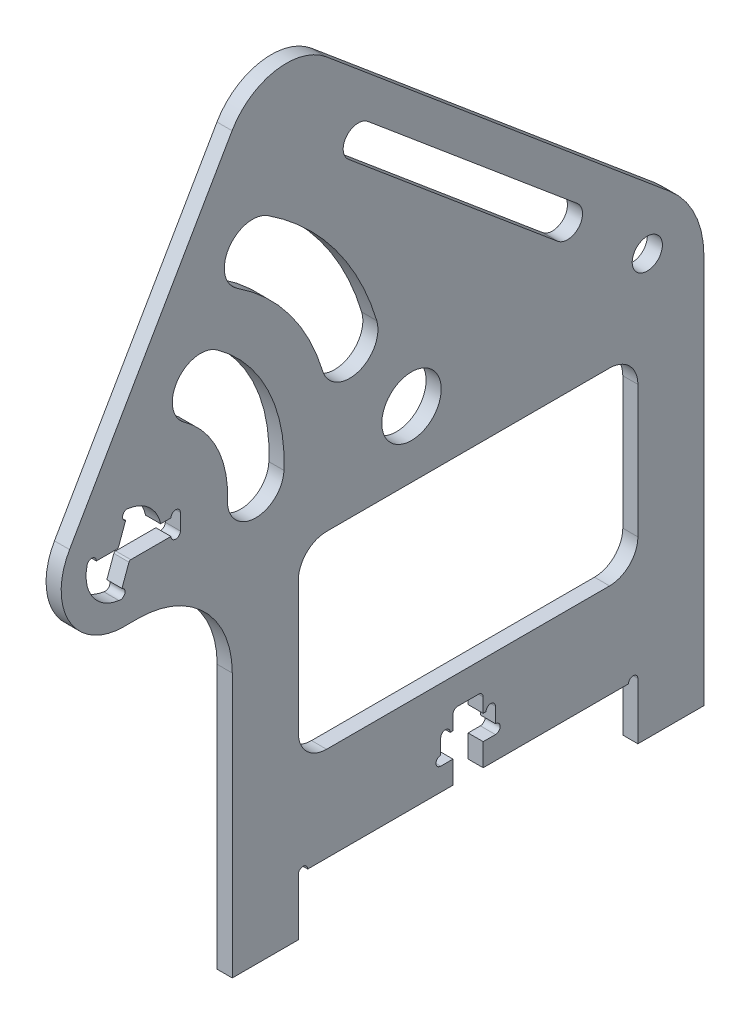
SolidWorks part; units mm, degrees
material "Thornel VCB-20 Carbon Cloth"
ref_plane "Front" through (0, 0, 0) normal (0, 0, 1) x (1, 0, 0)
ref_plane "Top" through (0, 0, 0) normal (0, 1, 0) x (1, 0, 0)
ref_plane "Right" through (0, 0, 0) normal (1, 0, 0) x (0, 0, -1)
sketch "Sketch1" plane through (0, 0, 0) normal (1, 0, 0) x (0, 0, -1)
  line L0 (-25, 0) -> (25, 0)
  line L1 (25, 0) -> (25, 40)
  line L2 (25, 40) -> (-21.0649, 78.653)
  line L3 (-21.0649, 78.653) -> (-48, 32)
  line L4 (-48, 32) -> (-25, 32)
  line L5 (-25, 32) -> (-25, 0)
  dimension "D1" = 50
  dimension "D2" = 32
  dimension "D3" = 60
  dimension "D4" = 40
  dimension "D5" = 40
  dimension "D6" = 23
extrude "main body" add sketch "Sketch1" against normal mid plane 1.6
sketch "Sketch2" plane through (0, 0, 0) normal (1, 0, 0) x (0, 0, -1)
  line L0 (0, 0) -> (0, -15.3449) construction
  line L1 (-25, 0) -> (-25, -6)
  line L2 (25, 0) -> (25, -6)
  line L3 (-25, -6) -> (-18, -6)
  line L4 (25, -6) -> (18, -6)
  line L5 (-18, -6) -> (-18, 0)
  line L6 (-25, 0) -> (25, 0) construction
  line L7 (18, -6) -> (18, 0)
  line L8 (-18, 0) -> (-25, 0)
  line L9 (18, 0) -> (25, 0)
  dimension "D1" = 7
  dimension "D2" = 6
extrude "slot tabs" add sketch "Sketch2" along normal up to surface and the other way up to surface up to face at (0.8, 30.4422, 11.5108) other way up to face at (-0.8, 30.4422, 11.5108)
sketch "Sketch10" [suppressed] plane through (0.8, 0, 0) normal (1, 0, 0) x (0, 0, -1)
  line L0 (-18, 0) -> (18, 0) construction
  line L1 (-18, 0) -> (18, 0) construction
  circle A0 centre (-17.2, 0) radius 0.8
  circle A1 centre (17.2, 0) radius 0.8
  dimension "D1" = 1.6
extrude "slot dogs" [suppressed] cut sketch "Sketch10" against normal through all
sketch "Sketch3" plane through (0, 0, 0) normal (1, 0, 0) x (0, 0, -1)
  line L0 (-1.6, 2.4) -> (-1.6, 0)
  line L1 (-1.6, 2.4) -> (1.6, 2.4) construction
  line L2 (-1.6, 0) -> (1.6, 0)
  line L3 (1.6, 2.4) -> (1.6, 0)
  line L4 (-1.6, 2.4) -> (1.6, 0) construction
  line L5 (-1.6, 0) -> (1.6, 2.4) construction
  line L6 (-18, 0) -> (18, 0) construction
  line L7 (-2.9, 2.4) -> (-1.6, 2.4)
  line L8 (2.9, 5) -> (-2.9, 5)
  line L9 (2.9, 5) -> (2.9, 2.4)
  line L10 (1.6, 2.4) -> (2.9, 2.4)
  line L11 (-2.9, 5) -> (-2.9, 2.4)
  line L12 (2.9, 5) -> (-2.9, 2.4) construction
  line L13 (2.9, 2.4) -> (-2.9, 5) construction
  line L14 (-1.6, 2.4) -> (2.9, 2.4) construction
  point P1 (0, 1.2)
  point P3 (0, 3.7)
  dimension "D1" = 3.2
  dimension "D2" = 2.4
  dimension "D3" = 5.8
  dimension "D4" = 2.6
extrude "attachment t-slot" cut sketch "Sketch3" against normal through all and the other way through all
sketch "camera slot positioning" plane through (0, 0, 0) normal (1, 0, 0) x (0, 0, -1)
  line L0 (-11.6418, 64.2191) -> (19, 38.5076)
  line L1 (25, 40) -> (-21.0649, 78.653) construction
  line L2 (25, 0) -> (25, 40) construction
  dimension "D1" = 5
  dimension "D2" = 6
  dimension "D3" = 40
sketch "Sketch5" plane through (0.8, 0, 0) normal (1, 0, 0) x (0, 0, -1)
  line L0 (-11.6418, 64.2191) -> (10.534, 45.6114) construction
  line L1 (-11.6418, 64.2191) -> (19, 38.5076) construction
  line L2 (-10.6133, 65.4447) -> (11.5624, 46.8371)
  line L3 (-12.6702, 62.9934) -> (9.5055, 44.3857)
  circle A0 centre (19, 38.5076) radius 1.6
  arc A1 (-10.6133, 65.4447) -> (-12.6702, 62.9934) centre (-11.6418, 64.2191) ccw
  arc A2 (9.5055, 44.3857) -> (11.5624, 46.8371) centre (10.534, 45.6114) ccw
  point P8 (-0.5539, 54.9152)
  dimension "D1" = 3.2
  dimension "D2" = 3.2
extrude "camera slot and standoff hole" cut sketch "Sketch5" against normal through all
sketch "Sketch6" plane through (0.8, 0, 0) normal (1, 0, 0) x (0, 0, -1)
  line L1 (-48, 32) -> (-36.5, 38.6395) construction
  line L2 (-40.3333, 45.2791) -> (-32.6667, 32) construction
  line L3 (-21.0649, 78.653) -> (-48, 32) construction
  line L4 (-48, 32) -> (-25, 32) construction
  line L5 (-36.5, 38.6395) -> (-36.5, 32) construction
  line L6 (-25, 32) -> (-25, -6) construction
  circle A0 centre (-36.5, 38.6395) radius 4
  dimension "D1" = 8
  dimension "D2" = 11.5
  dimension "D3" = 6.6395
extrude "camera plate hole" cut sketch "Sketch6" against normal through all
sketch "Sketch9" plane through (0.8, 0, 0) normal (1, 0, 0) x (0, 0, -1)
  line L0 (-30.5, 39.4895) -> (-34.5, 39.4895)
  line L1 (-30.5, 39.4895) -> (-30.5, 37.7895)
  line L2 (-34.5, 39.4895) -> (-34.5, 37.7895)
  line L3 (-30.5, 37.7895) -> (-34.5, 37.7895)
  line L4 (-30.5, 39.4895) -> (-34.5, 37.7895) construction
  line L5 (-34.5, 39.4895) -> (-30.5, 37.7895) construction
  line L6 (-32.5, 38.6395) -> (-36.5, 38.6395) construction
  line L7 (-36.5, 38.6395) -> (-40.5, 38.6395) construction
  circle A0 centre (-36.5, 38.6395) radius 4 construction
  circle A1 centre (-36.5, 38.6395) radius 4 construction
  point P1 (-32.5, 38.6395)
  dimension "D1" = 10
  dimension "D2" = 1.7
extrude "camera plate slot" cut sketch "Sketch9" against normal through all
sketch "Sketch11" plane through (0.8, 0, 0) normal (1, 0, 0) x (0, 0, -1)
  line L0 (-32.5914, 37.7895) -> (-35.9048, 37.7895)
  line L1 (-35.9048, 37.7895) -> (-37.0381, 34.6759)
  line L2 (-35.9619, 42.6032) -> (-35.9619, 45.1486)
  line L3 (-30.5, 32) -> (-30.5, 37.7895)
  line L4 (-30.5, 37.7895) -> (-32.5914, 37.7895)
  line L5 (-40.4086, 39.4895) -> (-37.0952, 39.4895)
  line L6 (-37.0952, 39.4895) -> (-35.9619, 42.6032)
  line L7 (-35.9619, 45.1486) -> (-40.4086, 45.1486)
  line L8 (-40.4086, 45.1486) -> (-40.4086, 39.4895)
  line L9 (-37.0952, 39.4895) -> (-35.9048, 37.7895)
  line L10 (-25, 32) -> (-25, -6) construction
  line L11 (-37.0381, 34.6759) -> (-37.0381, 32)
  line L12 (-37.0381, 32) -> (-30.5, 32)
  line L13 (-21.0649, 78.653) -> (-48, 32) construction
  line L14 (-48, 32) -> (-25, 32) construction
  line L16 (-34.5, 39.4895) -> (-34.5, 37.7895) construction
  line L17 (-34.5, 39.4895) -> (-34.5, 37.7895) construction
  line L18 (-35.1319, 42.3983) -> (-37.8681, 34.8808)
  arc A0 (-32.5914, 39.4895) -> (-32.5914, 37.7895) centre (-36.5, 38.6395) ccw construction
  point P26 (-36.5, 38.6395)
  arc M3 (-32.5914, 37.7895) -> (-32.5914, 39.4895) centre (-36.5, 38.6395) cw
  dimension "D1" = 1.7
  dimension "D2" = 1.7
  dimension "D3" = 20
  dimension "D4" = 1.7
extrude "angle guard" add sketch "Sketch11" against normal up to surface (1.6 mm away) contours L5 L6 M3 | L0 L1 M3 up to face at (-0.8, 38.6395, 33.5228)
sketch "Sketch7" plane through (0.8, 0, 0) normal (1, 0, 0) x (0, 0, -1)
  line L0 (-25, 0) -> (25, 0) construction
  line L1 (-18, 10) -> (18, 10)
  line L2 (-18, 10) -> (-18, 30)
  line L3 (-18, 30) -> (18, 30)
  line L4 (18, 10) -> (18, 30)
  line L5 (18, -6) -> (18, 0) construction
  line L6 (-18, 0) -> (-18, -6) construction
  line L8 (-48, 32) -> (-25, 32) construction
  dimension "D1" = 10
  dimension "D2" = 2
extrude "Cut-Extrude4" cut sketch "Sketch7" against normal through all
sketch "Sketch13" [suppressed] plane through (0.8, 0, 0) normal (1, 0, 0) x (0, 0, -1)
  line L3 (-40.4086, 39.4895) -> (-36.5, 38.6395) construction
  line L4 (-36.5, 38.6395) -> (-35.9619, 42.6032) construction
  line L5 (-36.5, 38.6395) -> (-36.9305, 35.4686) construction
  circle A0 centre (-39.6269, 39.3195) radius 0.8
  circle A1 centre (-36.0695, 41.8104) radius 0.8
  circle A2 centre (-36.9305, 35.4686) radius 0.8
  arc A3 (-32.5914, 39.4895) -> (-35.9619, 42.6032) centre (-36.5, 38.6395) ccw construction
  arc A4 (-40.4086, 39.4895) -> (-37.0381, 34.6759) centre (-36.5, 38.6395) ccw construction
  dimension "D1" = 1.6
extrude "camera plate hole dogs" [suppressed] cut sketch "Sketch13" against normal through all
fillet "camera plate hole ease" radius 0.2 2 edges at (0, 37.7895, 35.9048) (0, 39.4895, 37.0952)
fillet "access hole fillet" radius 3 4 edges at (0, 30, -18) (0, 10, -18) (0, 10, 18) (0, 30, 18)
fillet "secondary fillet" radius 10 2 edges at (0, 40, -25) (0, 32, 25)
fillet "camera edge fillet" radius 6.6395 2 edges at (0, 78.653, 21.0649) (0, 32, 48)
sketch "Sketch8" plane through (0.8, 0, 0) normal (1, 0, 0) x (0, 0, -1)
  circle A0 centre (-6, 37) radius 3.15
  dimension "D1" = 6.3
  dimension "D2" = 6
  dimension "D3" = 37
extrude "TX mount hole" cut sketch "Sketch8" against normal through all
sketch "Sketch14" plane through (0.8, 0, 0) normal (1, 0, 0) x (0, 0, -1)
  line L0 (-1.1, 7) -> (1.1, 7)
  line L1 (2.9, 5) -> (2.9, 2.4) construction
  line L2 (-2.9, 2.4) -> (-2.9, 5) construction
  line L3 (-18, 0) -> (-1.6, 0) construction
  line L4 (1.6, 0) -> (18, 0) construction
  line L5 (-37.0473, 39.6211) -> (-35.9619, 42.6032) construction
  line L6 (-40.4086, 39.4895) -> (-37.2352, 39.4895) construction
  line L7 (-35.9527, 37.6579) -> (-37.0381, 34.6759) construction
  line L8 (-35.7648, 37.7895) -> (-30.5, 37.7895) construction
  line L10 (-30.5, 39.4895) -> (-32.5914, 39.4895) construction
  line L11 (0, 5) -> (0, 7) construction
  line L12 (-2.9, 5) -> (2.9, 5) construction
  line L13 (-1.6, 5) -> (-1.6, 6.5)
  line L14 (1.6, 5) -> (1.6, 6.5)
  circle A0 centre (-2.4, 5) radius 0.5
  circle A1 centre (2.4, 5) radius 0.5
  circle A2 centre (2.9, 2.9) radius 0.5
  circle A3 centre (-2.9, 2.9) radius 0.5
  circle A4 centre (-17.5, 0) radius 0.5
  circle A5 centre (17.5, 0) radius 0.5
  circle A6 centre (-36.1329, 42.1333) radius 0.5
  circle A7 centre (-39.9086, 39.4895) radius 0.5
  circle A8 centre (-36.8671, 35.1457) radius 0.5
  circle A9 centre (-31, 37.7895) radius 0.5
  circle A10 centre (-31, 39.4895) radius 0.5
  arc A11 (-1.6, 5) -> (1.6, 5) centre (0, 5) ccw
  arc A12 (-1.6, 6.5) -> (-1.1, 7) centre (-1.1, 6.5) cw
  arc A13 (1.6, 6.5) -> (1.1, 7) centre (1.1, 6.5) ccw
  point P56 (0, 6)
  dimension "D1" = 1
  dimension "D2" = 3.2
  dimension "D3" = 1.5
extrude "Cut-Extrude5" cut sketch "Sketch14" against normal up to next
sketch "Sketch15" plane through (0.8, 0, 0) normal (1, 0, 0) x (0, 0, -1)
  line L0 (-25.0212, 71.8004) -> (-42.25, 41.9593) construction
  line L1 (15, 30) -> (-15, 30) construction
  arc A0 (-28.3549, 50.0263) -> (-22.5146, 38) centre (-36.5, 38.6395) cw construction
  arc A1 (-19.5177, 37.863) -> (-26.6096, 52.4663) centre (-36.5, 38.6395) ccw
  arc A2 (-25.5115, 38.137) -> (-30.1003, 47.5863) centre (-36.5, 38.6395) ccw
  arc A3 (-25.5115, 38.137) -> (-19.5177, 37.863) centre (-22.5146, 38) ccw
  arc A4 (-26.6096, 52.4663) -> (-30.1003, 47.5863) centre (-28.3549, 50.0263) ccw
  arc A5 (-22.8403, 59.5778) -> (-12.557, 45.8321) centre (-36.5, 38.6395) cw construction
  arc A6 (-9.6838, 46.6952) -> (-21.2012, 62.0904) centre (-36.5, 38.6395) ccw
  arc A7 (-15.4302, 44.969) -> (-24.4795, 57.0652) centre (-36.5, 38.6395) ccw
  arc A8 (-15.4302, 44.969) -> (-9.6838, 46.6952) centre (-12.557, 45.8321) ccw
  arc A9 (-21.2012, 62.0904) -> (-24.4795, 57.0652) centre (-22.8403, 59.5778) ccw
  circle A10 centre (-6, 37) radius 3.15 construction
  point P4 (-23.9065, 44.7553)
  point P16 (-16.4818, 53.6153)
  dimension "D1" = 14
  dimension "D2" = 6
  dimension "D3" = 8
  dimension "D5" = 11
  dimension "D6" = 8
  dimension "D7" = 11
  dimension "D4" = 8
extrude "Cut-Extrude6" cut sketch "Sketch15" against normal up to next
equation "\"D2@Sketch5\"=\"D1@Sketch5\""
equation "\"D1@Sketch11\"=\"D4@Sketch11\""
equation "\"D2@Sketch11\"=\"D1@Sketch11\""
equation "\"D1@camera edge fillet\"=\"D3@Sketch6\""
